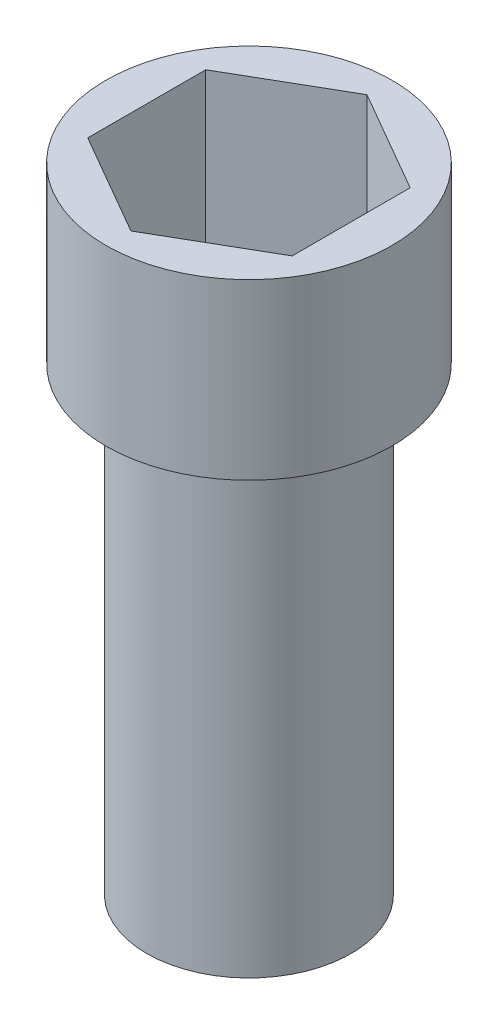
SolidWorks part; units mm, degrees
material "Alloy Steel"
ref_plane "Front Plane" through (0, 0, 0) normal (0, 0, 1) x (1, 0, 0)
ref_plane "Top Plane" through (0, 0, 0) normal (0, 1, 0) x (1, 0, 0)
ref_plane "Right Plane" through (0, 0, 0) normal (1, 0, 0) x (0, 0, -1)
sketch "Sketch1" plane through (0, 0, 0) normal (0, 1, 0) x (1, 0, 0)
  circle A0 centre (0, 0) radius 10
  dimension "D1" = 20
extrude "Boss-Extrude1" add sketch "Sketch1" along normal blind 45
sketch "Sketch2" plane through (0, 45, 0) normal (0, 1, 0) x (1, 0, 0)
  circle A0 centre (0, 0) radius 14
  dimension "D1" = 28
extrude "Boss-Extrude2" add sketch "Sketch2" along normal blind 17
sketch "Sketch3" plane through (0, 62, 0) normal (0, 1, 0) x (1, 0, 0)
  line L1 (0, 11.547) -> (-10, 5.7735)
  line L2 (-10, 5.7735) -> (-10, -5.7735)
  line L3 (-10, -5.7735) -> (0, -11.547)
  line L4 (0, -11.547) -> (10, -5.7735)
  line L5 (10, -5.7735) -> (10, 5.7735)
  line L6 (10, 5.7735) -> (0, 11.547)
  circle A0 centre (0, 0) radius 10 construction
  dimension "D1" = 20
extrude "Cut-Extrude1" cut sketch "Sketch3" against normal blind 16.5
